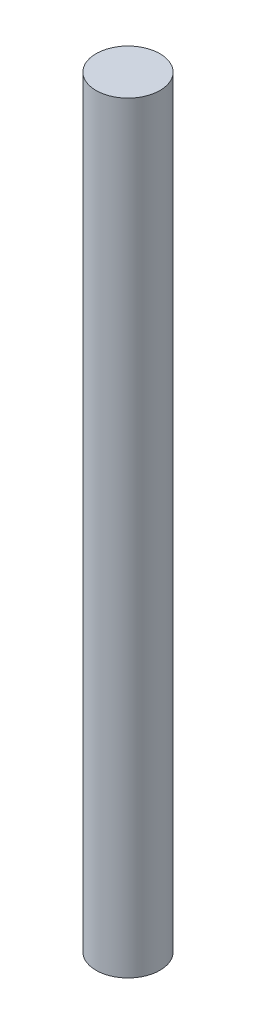
SolidWorks part; units mm, degrees
ref_plane "Front Plane" through (0, 0, 0) normal (0, 0, 1) x (1, 0, 0)
ref_plane "Top Plane" through (0, 0, 0) normal (0, 1, 0) x (1, 0, 0)
ref_plane "Right Plane" through (0, 0, 0) normal (1, 0, 0) x (0, 0, -1)
sketch "Sketch1" plane through (0, 0, 0) normal (0, 1, 0) x (1, 0, 0)
  circle A0 centre (0, 0) radius 1.905
  dimension "D1" = 3.81
extrude "Boss-Extrude1" add sketch "Sketch1" along normal blind 45.466
